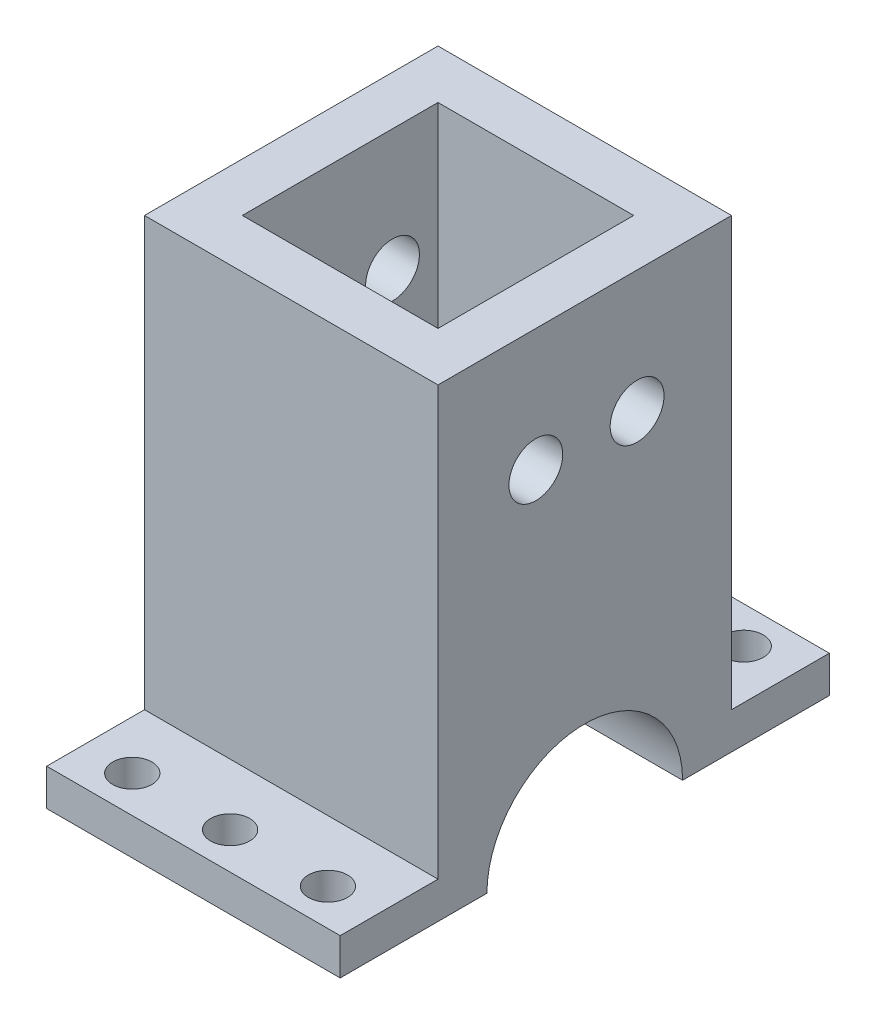
SolidWorks part; units mm, degrees
ref_plane "前视基准面" through (0, 0, 0) normal (0, 0, 1) x (1, 0, 0)
ref_plane "上视基准面" through (0, 0, 0) normal (0, 1, 0) x (1, 0, 0)
ref_plane "右视基准面" through (0, 0, 0) normal (1, 0, 0) x (0, 0, -1)
sketch "草图1" plane through (0, 0, 0) normal (0, 1, 0) x (1, 0, 0)
  line L0 (0, 0) -> (0, 16)
  line L1 (0, 0) -> (16, 0)
  line L2 (0, 16) -> (16, 16)
  line L3 (16, 0) -> (16, 16)
  line L6 (-4, 16) -> (-4, 20)
  line L7 (-4, 20) -> (0, 20)
  line L9 (20, -4) -> (20, 0)
  line L10 (16, -4) -> (20, -4)
  line L13 (-4, 20) -> (20, 20)
  line L14 (-4, 20) -> (-4, -4)
  line L15 (20, 20) -> (20, -4)
  line L16 (-4, -4) -> (20, -4)
extrude "凸台-拉伸1" add sketch "草图1" against normal blind 20 contours L14 L16 L10 L9 L15 L13 L7 L6 L3 L1 L0 L2
sketch "草图2" plane through (0, -20, 0) normal (0, -1, 0) x (1, 0, 0)
  line L4 (20, 4) -> (20, -20)
  line L5 (20, -20) -> (-4, -20)
  line L6 (-4, -20) -> (-4, 4)
  line L7 (-4, 4) -> (20, 4)
extrude "凸台-拉伸4" add sketch "草图2" along normal blind 10
sketch "草图3" plane through (-4, 0, 0) normal (-1, 0, 0) x (0, 0, 1)
  line L0 (4, -30) -> (-20, -30)
  line L1 (8, -38) -> (12, -38)
  line L2 (-24, -38) -> (-16, -38)
  line L3 (8, -38) -> (8, -35)
  line L4 (8, -35) -> (4, -35)
  line L5 (4, -35) -> (4, -30)
  line L6 (-24, -35) -> (-20, -35)
  line L7 (-24, -38) -> (-24, -35)
  line L8 (-20, -35) -> (-20, -30)
  line L9 (0, -38) -> (8, -38)
  line L10 (12, -38) -> (12, -35)
  line L11 (12, -35) -> (8, -35)
  line L12 (-24, -38) -> (-28, -38)
  line L13 (-28, -38) -> (-28, -35)
  line L14 (-28, -35) -> (-24, -35)
  arc A0 (0, -38) -> (-16, -38) centre (-8, -38) ccw
  line M5 (-20, -30) -> (4, -30)
extrude "凸台-拉伸6" add sketch "草图3" against normal blind 24 contours L10 L11 L3 L1 | A0 L9 L3 L4 L5 L0 | A0 L8 L6 L7 L2 M5 | L14 L13 L12 L7
sketch "草图5" plane through (0, -38, 0) normal (0, -1, 0) x (1, 0, 0)
  circle A0 centre (8, 9) radius 1.6
  circle A1 centre (16, 9) radius 1.6
  circle A2 centre (0, 9) radius 1.6
  circle A3 centre (0, -25) radius 1.6
  circle A4 centre (8, -25) radius 1.6
  circle A5 centre (16, -25) radius 1.6
extrude "切除-拉伸1" cut sketch "草图5" against normal blind 24
sketch "草图6" plane through (0, 0, 0) normal (1, 0, 0) x (0, 0, -1)
  circle A0 centre (12.2801, -10) radius 2.2
  circle A1 centre (4, -10) radius 2.2
extrude "切除-拉伸2" cut sketch "草图6" against normal mid plane 50
